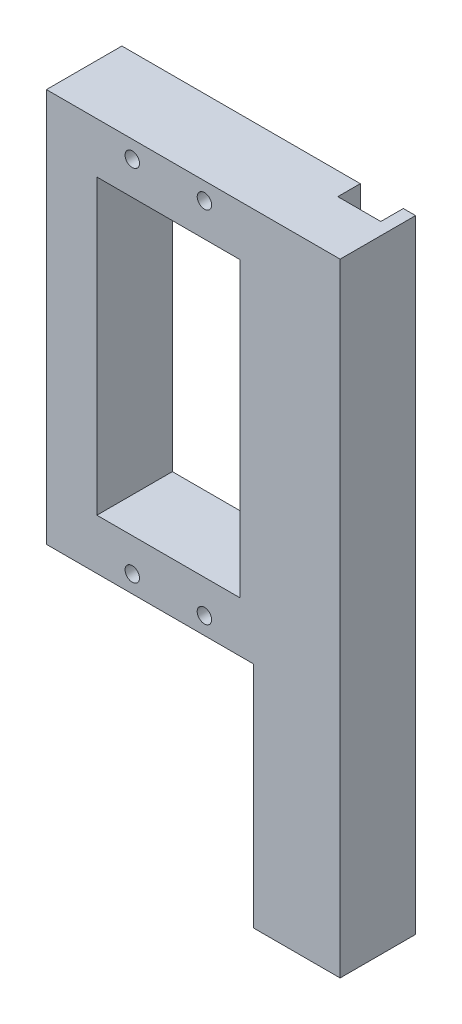
SolidWorks part; units mm, degrees
ref_plane "Front Plane" through (0, 0, 0) normal (0, 0, 1) x (1, 0, 0)
ref_plane "Top Plane" through (0, 0, 0) normal (0, 1, 0) x (1, 0, 0)
ref_plane "Right Plane" through (0, 0, 0) normal (1, 0, 0) x (0, 0, -1)
sketch "Sketch2" plane through (0, 0, 0) normal (0, 0, 1) x (1, 0, 0)
  line L0 (-9.9, -20.3) -> (9.9, -20.3)
  line L1 (9.9, -19.3) -> (9.9, -20.3)
  line L2 (9.9, -19.3) -> (9.9, 20.3)
  line L4 (9.9, 20.3) -> (-9.9, 20.3)
  line L7 (-9.9, 20.3) -> (-9.9, -20.3)
  line L9 (-7.9, 27.3) -> (23.8131, 27.3)
  line L10 (-7.9, 27.3) -> (-16.9, 27.3)
  line L11 (11.8131, -27.3) -> (11.8131, -59.0021)
  line L12 (-16.9, 27.3) -> (-16.9, -27.3)
  line L13 (-2.175, -27.3) -> (-16.9, -27.3)
  line L15 (-2.175, -27.3) -> (11.8131, -27.3)
  line L16 (11.8131, -59.0021) -> (23.8131, -59.0021)
  line L17 (23.8131, -59.0021) -> (23.8131, 27.3)
extrude "Boss-Extrude2" add sketch "Sketch2" along normal blind 10.46
sketch "Sketch4" plane through (0, 0, 10.46) normal (0, 0, 1) x (1, 0, 0)
  line L0 (17.8131, -59.0021) -> (17.2, -59.0021)
  line L1 (17.2, 27.3) -> (16.1509, 27.3)
  line L2 (23.8131, 27.3) -> (-16.9, 27.3) construction
  line L3 (16.1509, 27.3) -> (16.1509, -59.0021)
  line L4 (11.8131, -59.0021) -> (23.8131, -59.0021) construction
  line L5 (17.8131, -59.0021) -> (22.1131, -59.0021)
  line L6 (22.1131, -59.0021) -> (22.1131, 27.3)
  line L7 (22.1131, 27.3) -> (17.2, 27.3)
  line L8 (16.1509, -59.0021) -> (17.8131, -59.0021)
  line L9 (17.2, -59.0021) -> (16.1509, -59.0021)
extrude "Cut-Extrude1" cut sketch "Sketch4" against normal blind 3.12 contours L5 L6 L7 L1 L3 L9 L0
sketch "Sketch5" plane through (0, 0, 10.46) normal (0, 0, 1) x (1, 0, 0)
  circle A0 centre (-5, -24.9) radius 1
  circle A1 centre (5, -24.9) radius 1
  circle A2 centre (-5, 24.89) radius 1
  circle A3 centre (5, 24.89) radius 1
extrude "Cut-Extrude2" cut sketch "Sketch5" against normal blind 20
ref_plane "Plane1" through (0, 0, -10) normal (0, 0, -1) x (-1, 0, 0)
mirror "Mirror1" about plane through (0, 0, -10) normal (0, 0, -1) of bodies 104
sketch "Sketch6" plane through (0, 0, 0) normal (0, 0, -1) x (-1, 0, 0)
  line L1 (-23.8131, 27.3) -> (77.8135, 27.3)
  line L2 (-23.8131, 27.3) -> (-23.8131, -68.3453)
  line L3 (-23.8131, -68.3453) -> (77.8135, -68.3453)
  line L4 (77.8135, 27.3) -> (77.8135, -68.3453)
extrude "Cut-Extrude3" cut sketch "Sketch6" against normal blind 30
